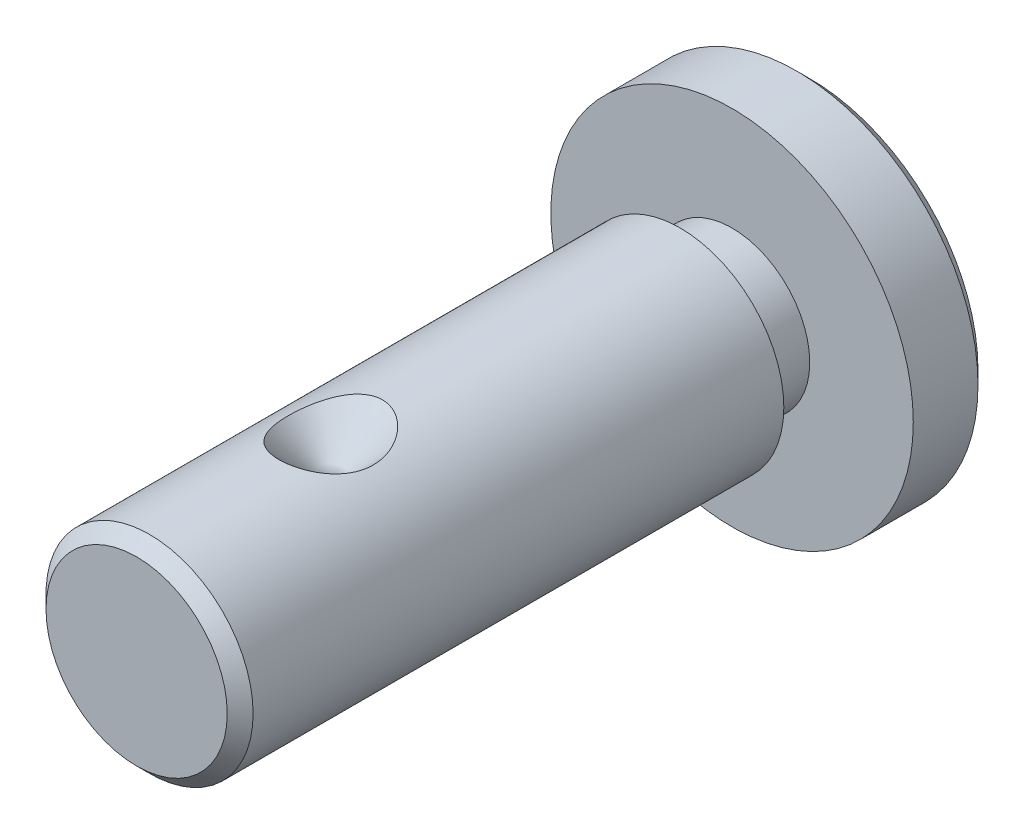
SolidWorks part; units mm, degrees
ref_plane "前视基准面" through (0, 0, 0) normal (0, 0, 1) x (1, 0, 0)
ref_plane "上视基准面" through (0, 0, 0) normal (0, 1, 0) x (1, 0, 0)
ref_plane "右视基准面" through (0, 0, 0) normal (1, 0, 0) x (0, 0, -1)
sketch "草图1" plane through (0, 0, 0) normal (0, 0, 1) x (1, 0, 0)
  circle A0 centre (0, 0) radius 7
  dimension "D1" = 14
extrude "凸台-拉伸1" add sketch "草图1" along normal blind 3
sketch "草图2" plane through (0, 0, 3) normal (0, 0, 1) x (1, 0, 0)
  circle A0 centre (0, 0) radius 4
  dimension "D1" = 8
extrude "凸台-拉伸2" add sketch "草图2" along normal blind 23
sketch "草图3" plane through (0, 0, 3) normal (0, 0, 1) x (1, 0, 0)
  circle A2 centre (0, 0) radius 3
  circle A3 centre (0, 0) radius 3
  dimension "D1" = 1
extrude "切除-拉伸1" cut sketch "草图3" along normal blind 2 flip side to cut
chamfer "倒角1" distance 0.5 angle 45 2 edges at (4, 0, 26) (7, 0, 0)
sketch "草图4" plane through (0, 0, 0) normal (1, 0, 0) x (0, 0, -1)
  line L0 (-18.5, 6.944) -> (-18.5, 1.1768) construction
  line L1 (-18.5, 2) -> (-16.5, 4)
  line L2 (-5, 4) -> (-25.5, 4) construction
  line L3 (-16.5, 4) -> (-18.5, 4)
  line L4 (-3, 7) -> (-3, -7) construction
  line L5 (-18.5, 2) -> (-18.5, 4)
  dimension "D1" = 45
  dimension "D2" = 2
  dimension "D3" = 15.5
revolve "切除-旋转1" cut sketch "草图4" angle 360 about L0
